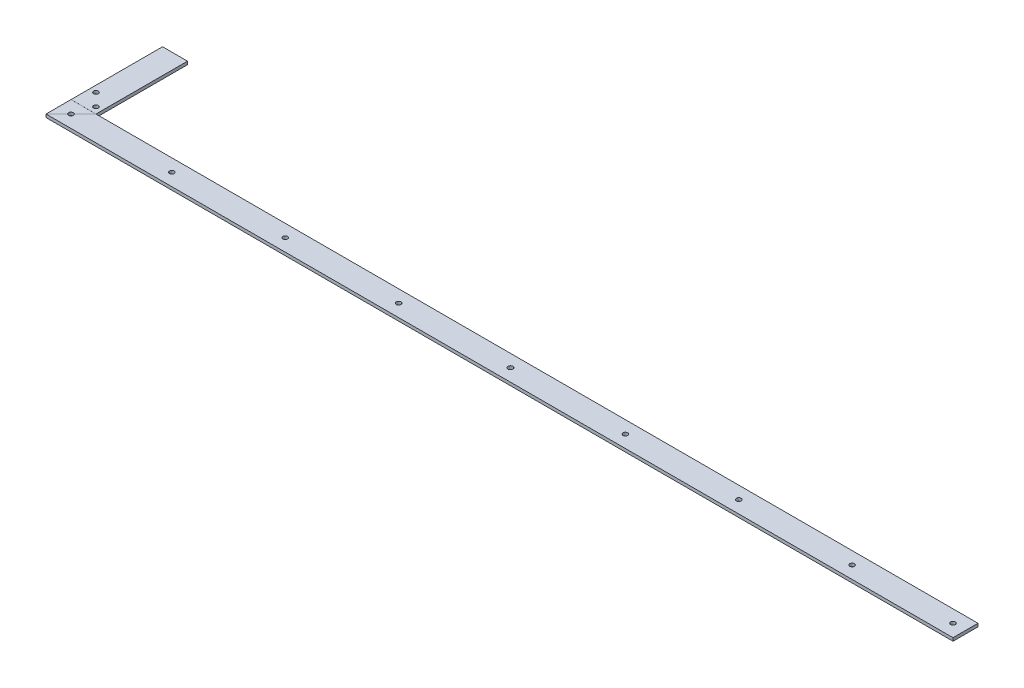
SolidWorks part; units mm, degrees
ref_plane "Alzado" through (0, 0, 0) normal (0, 0, 1) x (1, 0, 0)
ref_plane "Planta" through (0, 0, 0) normal (0, 1, 0) x (1, 0, 0)
ref_plane "Vista lateral" through (0, 0, 0) normal (1, 0, 0) x (0, 0, -1)
sketch "Croquis2" plane through (0, 0, 0) normal (0, 1, 0) x (1, 0, 0)
  line L1 (-25.4, 3.155) -> (25.4, 3.155)
  line L2 (-25.4, 3.155) -> (-25.4, -3.155)
  line L3 (-25.4, -3.155) -> (25.4, -3.155)
  line L4 (25.4, 3.155) -> (25.4, -3.155)
  line L5 (-25.4, 3.155) -> (25.4, -3.155) construction
  line L6 (-25.4, -3.155) -> (25.4, 3.155) construction
  line L7 (238.1, 3.155) -> (288.9, 3.155)
  line L8 (238.1, 3.155) -> (238.1, -3.155)
  line L9 (238.1, -3.155) -> (288.9, -3.155)
  line L10 (288.9, 3.155) -> (288.9, -3.155)
  line L11 (238.1, 3.155) -> (288.9, -3.155) construction
  line L12 (238.1, -3.155) -> (288.9, 3.155) construction
  point P0 (0, 0)
  point P6 (263.5, 0)
  dimension "D1" = 50.8
  dimension "D2" = 6.31
  dimension "D3" = 263.5
  dimension "D4" = 50.8
  dimension "D5" = 6.31
sketch3d "Croquis3D1"
  line L0 (0, 0, 0) -> (0, -567.24, 0)
  line L1 (0, -567.24, 0) -> (0, -567.24, 316.2)
  line L2 (0, -567.24, 316.2) -> (1786.7, -567.24, 316.2)
  line L3 (1786.7, -567.24, 316.2) -> (1786.7, -567.24, 578)
  line L4 (-25.4, 0, 0) -> (-25.4, -383.9185, 0) construction
  line L5 (-25.4, 0, -3.155) -> (-25.4, 0, 3.155) construction
  line L6 (-25.4, -383.9185, 0) -> (-25.4, -383.9185, 653.2834) construction
  line L7 (1786.7, -567.24, 578) -> (1786.7, -435.4728, 578)
  line L8 (1786.7, -435.4728, 578) -> (1786.7, -435.4728, 1432.0029)
  dimension "D1" = 567.24
  dimension "D2" = 316.2
  dimension "D3" = 1786.7
  dimension "D4" = 261.8
  dimension "D5" = 131.7672
  dimension "D6" = 854.0029
sweep "Barrer1" add profiles "Croquis2" path "Croquis3D1"
sketch "Croquis3" plane through (0, 0, -3.155) normal (0, 0, -1) x (-1, 0, 0)
  line L0 (-288.9, 0) -> (-288.9, -6.31)
  line L1 (-288.9, 0) -> (-288.9, -570.395) construction
  line L2 (-288.9, -6.31) -> (-238.1, -6.31)
  line L3 (-238.1, 0) -> (-238.1, -570.395) construction
  line L4 (-238.1, -6.31) -> (-238.1, 0)
  line L5 (-238.1, 0) -> (-288.9, 0)
  line L7 (-25.4, 0) -> (-25.4, -6.31)
  line L8 (-25.4, 0) -> (-25.4, -570.395) construction
  line L9 (-25.4, -6.31) -> (25.4, -6.31)
  line L10 (25.4, 0) -> (25.4, -570.395) construction
  line L11 (25.4, -6.31) -> (25.4, 0)
  line L12 (-25.4, 0) -> (25.4, 0) construction
  line L13 (25.4, 0) -> (-25.4, 0)
  dimension "D1" = 6.31
  dimension "D2" = 6.31
sketch3d "Croquis3D2"
  line L0 (25.4, -3.155, -3.155) -> (-0.201, -3.155, -3.155) construction
  line L1 (25.4, 0, -3.155) -> (25.4, -6.31, -3.155) construction
  line L2 (-0.201, -3.155, -3.155) -> (-0.201, -5.2746, -3.155) construction
  line L3 (-0.201, -3.155, -3.155) -> (-0.201, -3.155, -207.155)
  line L4 (-0.201, -3.155, -207.155) -> (-0.201, -53.155, -207.155)
  dimension "D1" = 204
  dimension "D2" = 50
sweep "Barrer4" add profiles "Croquis3" path "Croquis3D2"
sketch "Croquis4" plane through (0, 0, -210.31) normal (0, 0, -1) x (-1, 0, 0)
  line L0 (-238.1, 0) -> (-238.1, -53.155)
  line L1 (-238.1, -53.155) -> (-178.1, -53.155)
  line L2 (-178.1, -53.155) -> (-178.1, 0)
  line L3 (-178.1, 0) -> (-238.1, 0)
  dimension "D1" = 60
extrude "Saliente-Extruir1" add sketch "Croquis4" against normal blind 6.31
sketch "Croquis5" plane through (0, 0, -204) normal (0, 0, 1) x (1, 0, 0)
  line L0 (238.1, -6.31) -> (178.1, -6.31)
  line L1 (178.1, -53.155) -> (178.1, 0) construction
  line L2 (178.1, -6.31) -> (178.1, 0)
  line L3 (178.1, 0) -> (238.1, 0)
  line L4 (238.1, 0) -> (238.1, -6.31)
extrude "Cortar-Extruir1" cut sketch "Croquis5" against normal blind 6.31
sketch "Croquis6" plane through (0, -432.3178, 0) normal (0, 1, 0) x (1, 0, 0)
  circle A0 centre (1285.7, -1260.295) radius 4.75
  circle A1 centre (1495.7, -1260.295) radius 4.75
sketch "Croquis7" plane through (0, 0, 3.155) normal (0, 0, 1) x (1, 0, 0)
  line L0 (288.9, -564.085) -> (238.1, -564.085)
  line L1 (238.1, -564.085) -> (238.1, -68.8755)
  line L2 (238.1, 0) -> (238.1, -564.085) construction
  line L3 (238.1, -68.8755) -> (170.6111, -68.8755)
  line L4 (170.6111, -68.8755) -> (170.6111, 0)
  line L5 (170.6111, 0) -> (288.9, 0)
  line L6 (288.9, 0) -> (288.9, -564.085)
extrude "Cortar-Extruir2" cut sketch "Croquis7" against normal blind 502
sketch "Croquis8" plane through (0, 0, 3.155) normal (0, 0, 1) x (1, 0, 0)
  line L0 (25.4, -564.085) -> (-25.4, -564.085)
  line L1 (-25.4, -564.085) -> (-25.4, 0)
  line L2 (-25.4, 0) -> (25.4, 0)
  line L3 (25.4, 0) -> (25.4, -564.085)
extrude "Cortar-Extruir3" cut sketch "Croquis8" against normal blind 502
sketch "Croquis9" plane through (0, -432.3178, 0) normal (0, 1, 0) x (1, 0, 0)
  line L0 (1761.3, -341.6) -> (2075.6, -341.6)
  line L1 (2075.6, -27.3) -> (2075.6, -574.845) construction
  line L2 (2075.6, -341.6) -> (2075.6, -1432.0029)
  line L3 (2075.6, -1432.0029) -> (1761.3, -1432.0029)
  line L4 (1761.3, -341.6) -> (1761.3, -1432.0029)
extrude "Cortar-Extruir4" cut sketch "Croquis9" against normal blind 502
sketch "Croquis10" plane through (0, 0, -3.155) normal (0, 0, -1) x (-1, 0, 0)
  line L0 (-25.4, -564.085) -> (25.4, -564.085)
  line L1 (25.4, -564.085) -> (25.4, -570.395)
  line L2 (25.4, -570.395) -> (-25.4, -570.395)
  line L3 (-25.4, -570.395) -> (-25.4, -564.085)
extrude "Cortar-Extruir5" cut sketch "Croquis10" against normal blind 95
sketch "Croquis11" plane through (0, -564.085, 0) normal (0, 1, 0) x (1, 0, 0)
  line L0 (288.9, -27.3) -> (238.1, -27.3)
  line L1 (238.1, -3.155) -> (238.1, -78.1) construction
  line L2 (238.1, -78.1) -> (288.9, -78.1)
  line L3 (238.1, -78.1) -> (2024.8, -78.1) construction
  line L4 (288.9, -78.1) -> (288.9, -27.3)
  line L5 (288.9, -27.3) -> (288.9, 3.155)
  line L6 (288.9, 3.155) -> (238.1, 3.155)
  line L7 (238.1, 3.155) -> (238.1, -27.3)
  line M1 (288.9, -27.3) -> (288.9, -3.155)
  line M2 (288.9, -3.155) -> (288.9, 3.155)
  line M3 (288.9, 3.155) -> (238.1, 3.155)
  line M4 (238.1, 3.155) -> (238.1, -3.155)
  line M5 (238.1, -3.155) -> (238.1, -78.1)
  line M6 (238.1, -78.1) -> (288.9, -27.3)
extrude "Cortar-Extruir6" cut sketch "Croquis11" against normal blind 95 contours L2 L4 M6 | L0 M6 M5 | L0 M1 M2 M3 M4 M5
sketch "Croquis13" plane through (0, -564.085, 0) normal (0, 1, 0) x (1, 0, 0)
  line L0 (-25.4, -91.845) -> (-25.4, -341.6)
  line L1 (-25.4, -341.6) -> (94.6, -341.6)
  line L2 (-25.4, -341.6) -> (1761.3, -341.6) construction
  line L3 (94.6, -341.6) -> (94.6, -91.845)
  line L4 (94.6, -91.845) -> (-25.4, -91.845)
  dimension "D1" = 120
extrude "Cortar-Extruir7" cut sketch "Croquis13" against normal blind 95
sketch "Croquis16" plane through (0, -564.085, 0) normal (0, 1, 0) x (1, 0, 0)
  line L2 (288.9, -27.3) -> (163.9, -27.3)
  line L3 (163.9, -27.3) -> (163.9, -78.1)
  line L4 (163.9, -78.1) -> (288.9, -78.1)
  line L5 (288.9, -27.3) -> (288.9, -78.1)
  dimension "D1" = 125
extrude "Saliente-Extruir4" add sketch "Croquis16" against normal blind 6.31
sketch "Croquis17" plane through (94.6, 0, 0) normal (-1, 0, 0) x (0, 0, 1)
  line L0 (290.8, -564.085) -> (290.8, -570.395)
  line L1 (290.8, -570.395) -> (341.6, -570.395)
  line L2 (341.6, -570.395) -> (341.6, -564.085)
  line L3 (341.6, -564.085) -> (290.8, -564.085)
  line L4 (316.2, -564.085) -> (316.2, -570.395) construction
  line L5 (316.2, -570.395) -> (316.2, -567.24) construction
  line L6 (316.2, -567.24) -> (341.6, -567.24) construction
sketch3d "Croquis3D3"
  line L0 (94.6, -567.24, 316.2) -> (46.55, -567.24, 316.2)
  line L1 (46.55, -567.24, 316.2) -> (46.55, -567.24, 105.72)
  dimension "D1" = 48.05
  dimension "D2" = 210.48
sweep "Barrer5" add profiles "Croquis17" path "Croquis3D3"
sketch "Croquis18" plane through (21.15, 0, 0) normal (-1, 0, 0) x (0, 0, 1)
  line L0 (98.7872, -564.085) -> (98.7872, -435.523)
  line L1 (341.6, -564.085) -> (105.72, -564.085) construction
  line L2 (98.7872, -435.523) -> (64.97, -367.6227)
  line L3 (64.97, -367.6227) -> (59.3217, -370.4358)
  line L4 (59.3217, -370.4358) -> (91.8975, -435.8435)
  line L5 (91.8975, -435.8435) -> (91.8429, -564.085)
  line L6 (91.8429, -564.085) -> (98.7872, -564.085)
  dimension "D1" = 6.31
extrude "Saliente-Extruir5" add sketch "Croquis18" against normal blind 50.8
sketch "Croquis20" plane through (163.9, 0, 0) normal (-1, 0, 0) x (0, 0, 1)
  line L0 (78.1, -564.085) -> (78.1, -439.8845)
  line L1 (78.1, -439.8845) -> (59.9661, -387.9255)
  line L2 (59.9661, -387.9255) -> (54.0085, -390.0047)
  line L3 (54.0085, -390.0047) -> (71.79, -440.954)
  line L4 (71.79, -440.954) -> (71.79, -564.085)
  line L5 (27.3, -564.085) -> (78.1, -564.085) construction
  line L6 (71.79, -564.085) -> (78.1, -564.085)
  dimension "D1" = 6.31
  dimension "D2" = 6.31
extrude "Saliente-Extruir6" add sketch "Croquis20" against normal blind 50.8
sketch "Croquis21" plane through (0, -564.085, 0) normal (0, 1, 0) x (1, 0, 0)
  line L0 (1812.1, -290.8) -> (1802.1, -290.8)
  line L1 (71.95, -290.8) -> (1812.1, -290.8) construction
  line L2 (1802.1, -290.8) -> (1802.1, -341.6)
  line L3 (1761.3, -341.6) -> (1812.1, -341.6) construction
  line L4 (1802.1, -341.6) -> (1812.1, -341.6)
  line L5 (1812.1, -341.6) -> (1812.1, -290.8)
  dimension "D1" = 10
extrude "Cortar-Extruir9" cut sketch "Croquis21" against normal blind 53
sketch "Croquis22" plane through (0, -564.085, 0) normal (0, 1, 0) x (1, 0, 0)
  line L1 (71.95, -290.8) -> (71.95, -341.6)
  line L2 (21.15, -341.6) -> (1761.3, -341.6) construction
  line L3 (71.95, -341.6) -> (72.05, -341.6)
  line L4 (72.05, -341.6) -> (72.05, -290.8)
  line L5 (71.95, -290.8) -> (1802.1, -290.8) construction
  line L6 (72.05, -290.8) -> (71.95, -290.8)
  dimension "D1" = 0.1
extrude "Cortar-Extruir10" cut sketch "Croquis22" against normal blind 10
sketch "Croquis23" plane through (0, -570.395, 0) normal (0, -1, 0) x (1, 0, 0)
  line L0 (2024.8, 341.6) -> (2024.8, 78.1)
  line L1 (2024.8, 78.1) -> (163.9, 78.1)
  line L2 (163.9, 78.1) -> (163.9, 0)
  line L3 (163.9, 0) -> (2111.3004, 0)
  line L4 (2111.3004, 0) -> (2111.3004, 341.6)
  line L5 (2111.3004, 341.6) -> (2024.8, 341.6)
extrude "Cortar-Extruir11" cut sketch "Croquis23" against normal blind 237
sketch "Croquis24" plane through (0, 0, 98.7872) normal (0, 0, 1) x (1, 0, 0)
  line L0 (21.15, -564.085) -> (71.95, -564.085)
  line L1 (71.95, -564.085) -> (71.95, -359.0988)
  line L2 (71.95, -359.0988) -> (21.15, -359.0988)
  line L3 (21.15, -359.0988) -> (21.15, -564.085)
extrude "Cortar-Extruir12" cut sketch "Croquis24" against normal blind 237
sketch "Croquis25" plane through (0, 0, 105.72) normal (0, 0, -1) x (-1, 0, 0)
  line L0 (-71.95, -570.395) -> (-71.95, -564.085)
  line L1 (-71.95, -564.085) -> (-21.15, -564.085)
  line L2 (-21.15, -564.085) -> (-21.15, -570.395)
  line L3 (-21.15, -570.395) -> (-71.95, -570.395)
extrude "Saliente-Extruir7" add sketch "Croquis25" along normal blind 1.1
sketch "Croquis26" plane through (1802.1, 0, 0) normal (1, 0, 0) x (0, 0, -1)
  line L0 (-341.6, -564.085) -> (-341.6, -570.395)
  line L1 (-341.6, -570.395) -> (-290.8, -570.395)
  line L2 (-290.8, -570.395) -> (-290.8, -564.085)
  line L3 (-290.8, -564.085) -> (-341.6, -564.085)
extrude "Saliente-Extruir8" add sketch "Croquis26" along normal blind 12.7
sketch "Croquis27" plane through (0, -564.085, 0) normal (0, 1, 0) x (1, 0, 0)
  line L0 (940.2, -316.2) -> (948.9952, -313.3353) construction
  circle A0 centre (940.2, -316.2) radius 5
  dimension "D1" = 10
extrude "Cortar-Extruir13" cut sketch "Croquis27" against normal blind 10
sketch "Croquis28" plane through (0, -564.085, 0) normal (0, 1, 0) x (1, 0, 0)
  line L0 (71.95, -341.6) -> (72.05, -341.6)
  line L1 (72.05, -341.6) -> (72.05, -290.8)
  line L2 (72.05, -290.8) -> (71.95, -290.8)
  line L3 (71.95, -290.8) -> (71.95, -341.6)
extrude "Saliente-Extruir9" add sketch "Croquis28" against normal up to surface (6.31 mm away)
sketch "Croquis29" plane through (0, -564.085, 0) normal (0, 1, 0) x (1, 0, 0)
  line L0 (71.95, -290.8) -> (21.15, -290.8)
  line L1 (21.15, -341.6) -> (21.15, -104.62) construction
  line L2 (21.15, -290.8) -> (21.15, -290.7)
  line L3 (21.15, -290.7) -> (71.95, -290.7)
  line L4 (71.95, -290.8) -> (71.95, -104.62) construction
  line L5 (71.95, -290.7) -> (71.95, -290.8)
  dimension "D1" = 0.1
extrude "Cortar-Extruir14" cut sketch "Croquis29" against normal blind 50
sketch "Croquis30" plane through (1814.8, 0, 0) normal (1, 0, 0) x (0, 0, -1)
  line L0 (-341.6, -564.085) -> (-341.6, -570.395)
  line L1 (-341.6, -570.395) -> (-290.8, -570.395)
  line L2 (-290.8, -570.395) -> (-290.8, -564.085)
  line L3 (-290.8, -564.085) -> (-341.6, -564.085)
extrude "Saliente-Extruir10" add sketch "Croquis30" along normal blind 50.8
sketch "Croquis31" plane through (0, -564.085, 0) normal (0, 1, 0) x (1, 0, 0)
  line L0 (1865.6, -316.2) -> (1840.2, -316.2) construction
  line L1 (1865.6, -290.8) -> (1865.6, -341.6) construction
  line L2 (1840.2, -316.2) -> (1840.2, -290.8) construction
  line L3 (1865.6, -290.8) -> (71.95, -290.8) construction
  circle A0 centre (1840.2, -316.2) radius 4.7625
  dimension "D2" = 9.525
  dimension "D1" = 25.4
extrude "Cortar-Extruir15" cut sketch "Croquis31" against normal blind 10
sketch "Croquis32" plane through (0, -564.085, 0) normal (0, 1, 0) x (1, 0, 0)
  line L0 (21.15, -316.2) -> (71.95, -316.2) construction
  line L1 (21.15, -341.6) -> (21.15, -290.8) construction
  line L2 (71.95, -316.2) -> (46.55, -316.2) construction
  line L3 (46.55, -316.2) -> (46.55, -290.8) construction
  line L4 (21.15, -290.8) -> (71.95, -290.8) construction
  circle A0 centre (46.55, -316.2) radius 4.7625
  dimension "D1" = 9.525
extrude "Cortar-Extruir16" cut sketch "Croquis32" against normal blind 33
sketch "Croquis33" plane through (0, -570.395, 0) normal (0, -1, 0) x (-1, 0, 0)
  circle A0 centre (-33.85, -252.7) radius 4.7625
  circle A1 centre (-59.25, -278.1) radius 4.7625
extrude "Cortar-Extruir17" cut sketch "Croquis33" against normal blind 50
sketch "Croquis34" plane through (0, -564.085, 0) normal (0, 1, 0) x (1, 0, 0)
  line L0 (1865.6, -316.2) -> (21.15, -316.2) construction
  line L1 (1865.6, -290.8) -> (1865.6, -341.6) construction
  line L2 (21.15, -341.6) -> (21.15, -290.8) construction
  line L3 (21.15, -316.2) -> (943.375, -316.2) construction
  line L4 (943.375, -316.2) -> (482.2625, -316.2) construction
  line L5 (482.2625, -316.2) -> (21.15, -316.2) construction
  line L6 (21.15, -316.2) -> (251.7063, -316.2) construction
  line L7 (482.2625, -316.2) -> (943.375, -316.2) construction
  line L8 (943.375, -316.2) -> (712.8187, -316.2) construction
  line L9 (943.375, -316.2) -> (1865.6, -316.2) construction
  line L10 (1865.6, -316.2) -> (1404.4875, -316.2) construction
  line L11 (1865.6, -316.2) -> (1404.4875, -316.2) construction
  line L12 (1404.4875, -316.2) -> (1635.0437, -316.2) construction
  line L13 (1635.0437, -316.2) -> (1635.0437, -245.0018) construction
  line L14 (1404.4875, -316.2) -> (943.375, -316.2) construction
  line L15 (943.375, -316.2) -> (1173.9312, -316.2) construction
  circle A0 centre (1635.0437, -316.2) radius 4.7625
  circle A1 centre (1404.4875, -316.2) radius 4.7625
  circle A2 centre (1173.9312, -316.2) radius 4.7625
  circle A3 centre (712.8187, -316.2) radius 4.7625
  circle A4 centre (482.2625, -316.2) radius 4.7625
  circle A5 centre (251.7063, -316.2) radius 4.7625
  dimension "D1" = 9.525
  dimension "D2" = 9.525
  dimension "D3" = 9.525
  dimension "D4" = 9.525
  dimension "D5" = 9.525
  dimension "D6" = 9.525
extrude "Cortar-Extruir18" cut sketch "Croquis34" against normal blind 82
